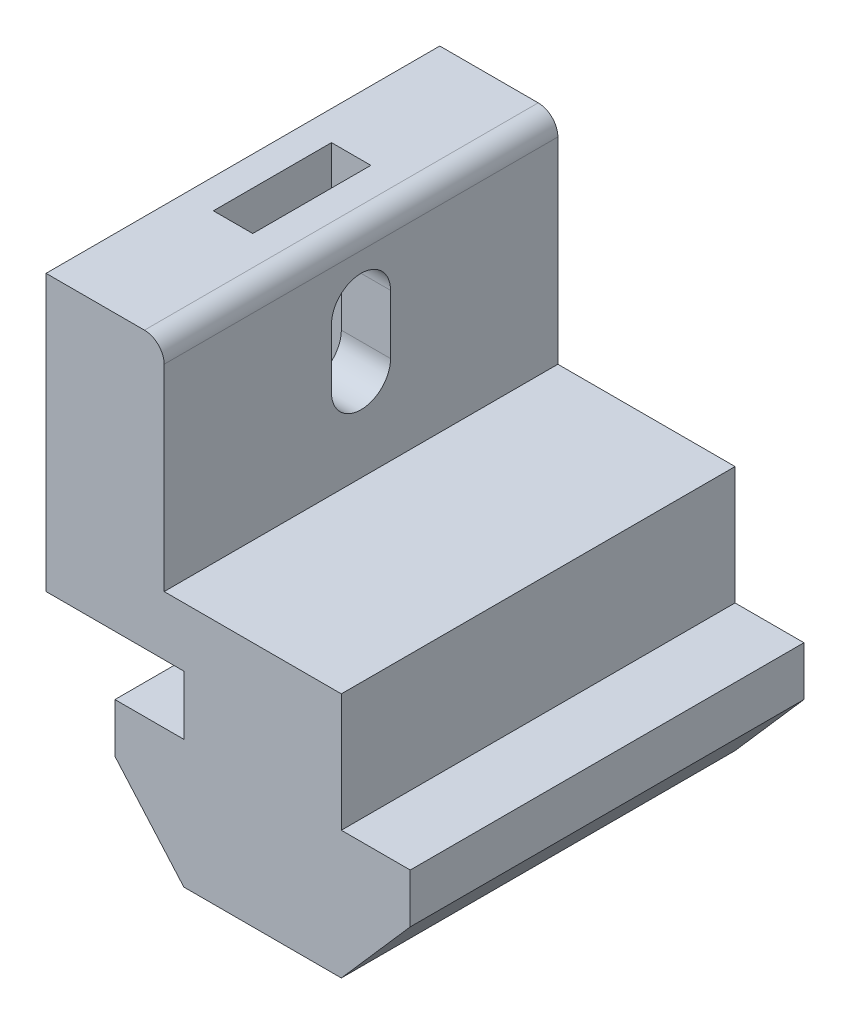
SolidWorks part; units mm, degrees
ref_plane "Piano frontale" through (0, 0, 0) normal (0, 0, 1) x (1, 0, 0)
ref_plane "Piano superiore" through (0, 0, 0) normal (0, 1, 0) x (1, 0, 0)
ref_plane "Piano destro" through (0, 0, 0) normal (1, 0, 0) x (0, 0, -1)
sketch "Schizzo2" plane through (0, 0, 0) normal (0, 0, 1) x (1, 0, 0)
  line L0 (0, 0) -> (0, 12.9875) construction
  line L1 (-4, 9.5) -> (-11, 9.5)
  line L2 (-11, 9.5) -> (-11, 23.5)
  line L3 (-11, 23.5) -> (-6, 23.5)
  line L4 (-5, 22.5) -> (-5, 12.5)
  line L5 (-5, 12.5) -> (4, 12.5)
  line L6 (4, 12.5) -> (4, 9.5)
  line L13 (-4, 0) -> (4, 0)
  line L14 (-7.5, 4) -> (-4, 0)
  line L15 (-7.5, 6.5) -> (-7.5, 4)
  line L16 (-4, 6.5) -> (-7.5, 6.5)
  line L17 (-4, 9.5) -> (-4, 6.5)
  line L44 (7.5, 4) -> (4, 0)
  line L45 (7.5, 6.5) -> (7.5, 4)
  line L46 (4, 6.5) -> (7.5, 6.5)
  line L72 (4, 9.5) -> (4, 6.5)
  arc A0 (-6, 23.5) -> (-5, 22.5) centre (-6, 22.5) cw
  point P9 (-5, 23.5)
  dimension "D11" = 1
  dimension "D1" = 8
  dimension "D2" = 4
  dimension "D3" = 2.5
  dimension "D4" = 8
  dimension "D5" = 3
  dimension "D6" = 15
  dimension "D7" = 11
  dimension "D8" = 6
  dimension "D9" = 3
  dimension "D10" = 14
extrude "Estrusione-Estrusione1" add sketch "Schizzo2" against normal blind 20
sketch "Schizzo6" plane through (-11, 0, 0) normal (-1, 0, 0) x (0, 0, 1)
  line L0 (0, 23.5) -> (0, 9.5) construction
  line L1 (-20, 23.5) -> (0, 23.5) construction
  line L2 (-10, 20) -> (-10, 17) construction
  line L3 (-8.5, 20) -> (-8.5, 17)
  line L4 (-11.5, 20) -> (-11.5, 17)
  line L5 (-20, 9.5) -> (0, 9.5) construction
  arc A1 (-8.5, 20) -> (-11.5, 20) centre (-10, 20) ccw
  arc A2 (-11.5, 17) -> (-8.5, 17) centre (-10, 17) ccw
  point P6 (-10, 18.5)
  dimension "D2" = 1.5
  dimension "D1" = 10
  dimension "D3" = 3.5
  dimension "D4" = 3
  dimension "D5" = 9
extrude "Taglio-Estrusione1" cut sketch "Schizzo6" against normal up to next
sketch "Schizzo11" plane through (0, 0, -20) normal (0, 0, -1) x (-1, 0, 0)
  line L0 (4, 0) -> (-4, 0) construction
  line L1 (7.5, 6.5) -> (7.5, 4) construction
  text T0 "3" font "Century Gothic" height 6.5
  dimension "D1" = 1
  dimension "D2" = 10.5
extrude "Estrusione-Estrusione4" add sketch "Schizzo11" along normal blind 0.6
sketch "Schizzo12" plane through (0, 23.5, 0) normal (0, 1, 0) x (1, 0, 0)
  line L0 (-6, 10) -> (-11, 10) construction
  line L1 (-6, 20) -> (-6, 0) construction
  line L2 (-11, 20) -> (-11, 0) construction
  line L4 (-7.5, 7) -> (-9.5, 7)
  line L5 (-7.5, 7) -> (-7.5, 13)
  line L6 (-7.5, 13) -> (-9.5, 13)
  line L7 (-9.5, 7) -> (-9.5, 13)
  line L8 (-7.5, 7) -> (-9.5, 13) construction
  line L9 (-7.5, 13) -> (-9.5, 7) construction
  point P6 (-8.5, 10)
  dimension "D1" = 2
  dimension "D2" = 6
extrude "Taglio-Estrusione2" cut sketch "Schizzo12" against normal blind 11
